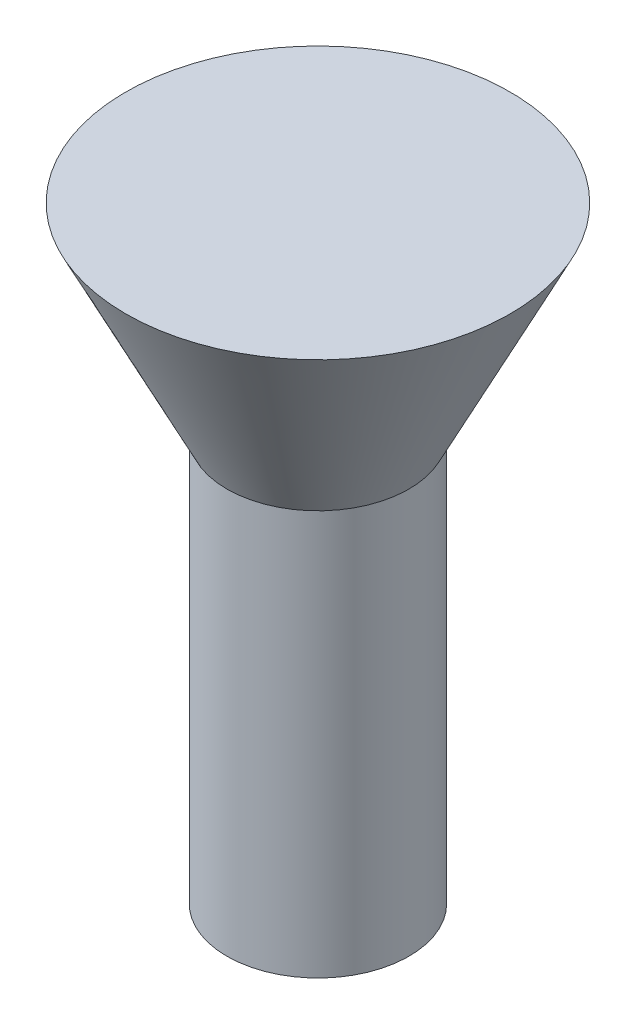
SolidWorks part; units mm, degrees
ref_plane "Alzado" through (0, 0, 0) normal (0, 0, 1) x (1, 0, 0)
ref_plane "Planta" through (0, 0, 0) normal (0, 1, 0) x (1, 0, 0)
ref_plane "Vista lateral" through (0, 0, 0) normal (1, 0, 0) x (0, 0, -1)
sketch "Croquis1" plane through (0, 0, 0) normal (0, 1, 0) x (1, 0, 0)
  circle A0 centre (0, 0) radius 4.5
  dimension "D1" = 9
extrude "Saliente-Extruir1" add sketch "Croquis1" along normal blind 20
ref_plane "Plano1" through (0, 30, 0) normal (0, 1, 0) x (1, 0, 0)
sketch "Croquis2" plane through (0, 30, 0) normal (0, 1, 0) x (1, 0, 0)
  circle A0 centre (0, 0) radius 9.5
  dimension "D1" = 19
loft "Recubrir1" add profiles "Croquis2" section "Croquis2" section face at (0, 20, 4.5)
